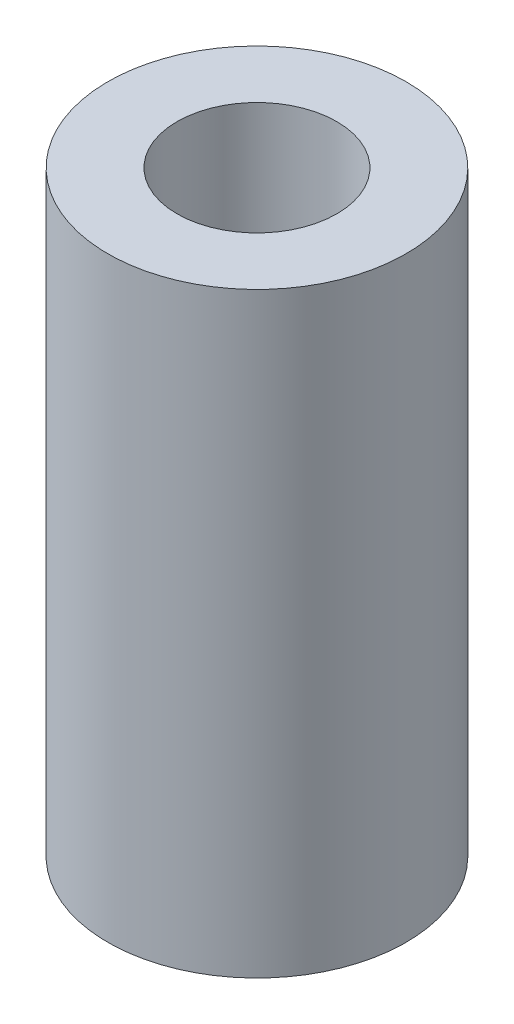
SolidWorks part; units mm, degrees
ref_plane "Front Plane" through (0, 0, 0) normal (0, 0, 1) x (1, 0, 0)
ref_plane "Top Plane" through (0, 0, 0) normal (0, 1, 0) x (1, 0, 0)
ref_plane "Right Plane" through (0, 0, 0) normal (1, 0, 0) x (0, 0, -1)
sketch "Sketch1" plane through (0, 0, 0) normal (0, 1, 0) x (1, 0, 0)
  circle A0 centre (0, 0) radius 2.5527
  circle A2 centre (0, 0) radius 4.7625
  dimension "D1" = 5.1054
  dimension "D2" = 9.525
extrude "Boss-Extrude1" add sketch "Sketch1" along normal blind 19.05
